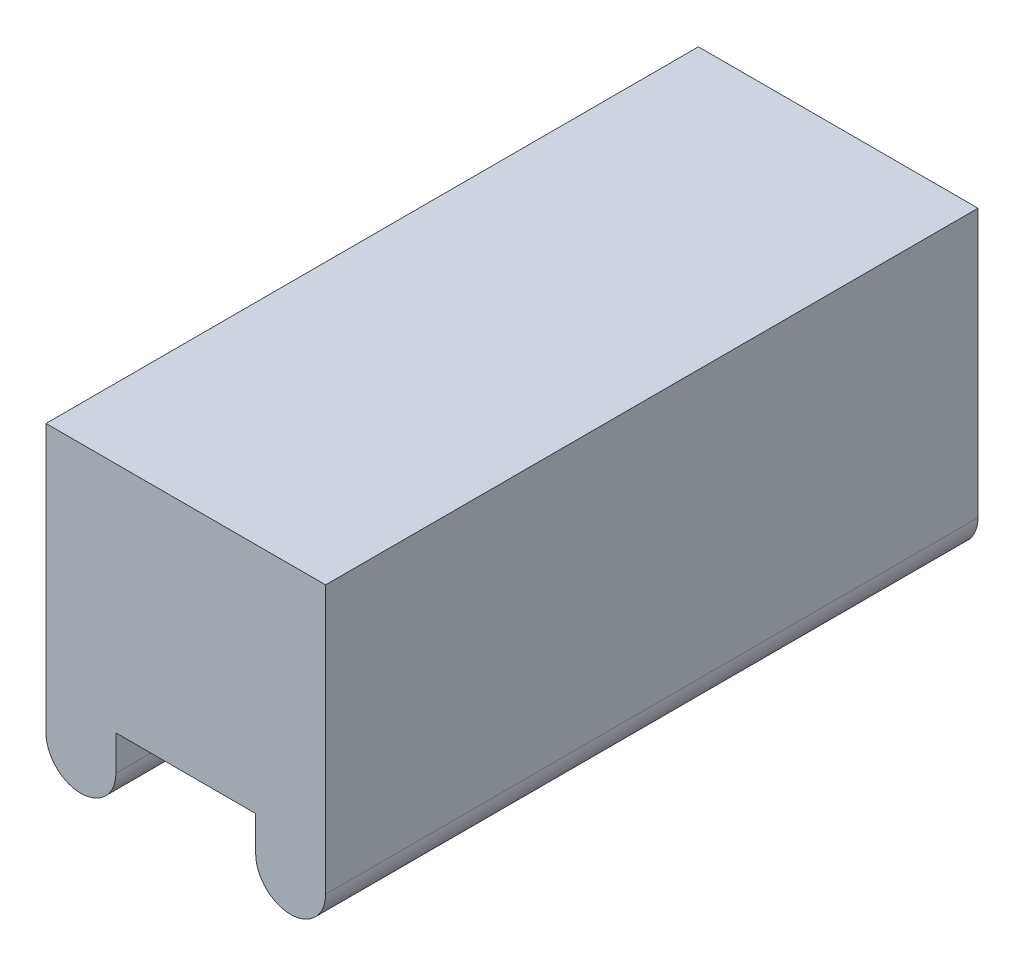
SolidWorks part; units mm, degrees
ref_plane "Front Plane" through (0, 0, 0) normal (0, 0, 1) x (1, 0, 0)
ref_plane "Top Plane" through (0, 0, 0) normal (0, 1, 0) x (1, 0, 0)
ref_plane "Right Plane" through (0, 0, 0) normal (1, 0, 0) x (0, 0, -1)
sketch "Sketch1" plane through (0, 0, 0) normal (0, 0, 1) x (1, 0, 0)
  line L0 (-3, -5) -> (3, -5)
  line L1 (6, -5) -> (6, 5)
  line L4 (-6, -5) -> (-6, 5)
  line L5 (-6, 5) -> (6, 5)
  line L8 (-3, -6.5) -> (-3, -5)
  line L11 (6, -6.5) -> (6, -5)
  line L16 (-6, -6.5) -> (-6, -5)
  line L17 (3, -6.5) -> (3, -5)
  arc A0 (-6, -6.5) -> (-3, -6.5) centre (-4.5, -6.5) ccw
  arc A1 (6, -6.5) -> (3, -6.5) centre (4.5, -6.5) cw
  dimension "D1" = 12
  dimension "D2" = 6
  dimension "D3" = 10
  dimension "D4" = 5
extrude "Boss-Extrude1" add sketch "Sketch1" along normal blind 28
